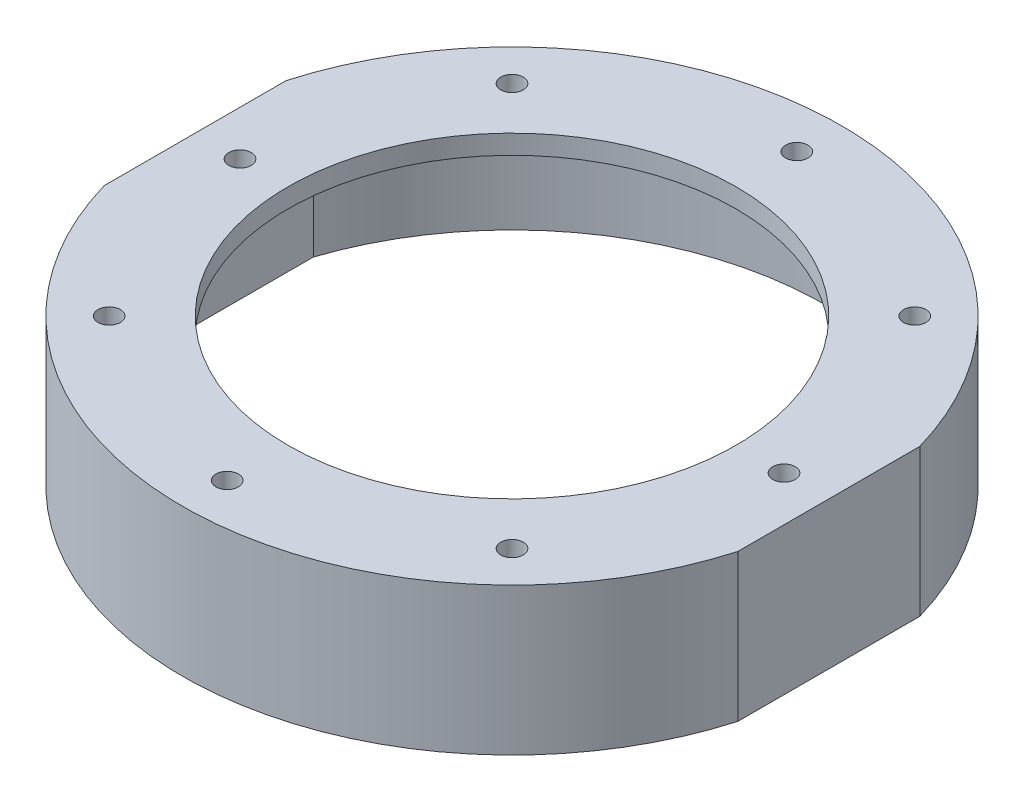
SolidWorks part; units mm, degrees
ref_plane "前视基准面" through (0, 0, 0) normal (0, 0, 1) x (1, 0, 0)
ref_plane "上视基准面" through (0, 0, 0) normal (0, 1, 0) x (1, 0, 0)
ref_plane "右视基准面" through (0, 0, 0) normal (1, 0, 0) x (0, 0, -1)
other "Configuration Table"
sketch "草图1" plane through (0, 0, 0) normal (0, 1, 0) x (1, 0, 0)
  line L1 (-46.5, -20.9132) -> (46.5, -20.9132)
  line L2 (-46.5, -20.9132) -> (-46.5, 20.9132)
  line L3 (-46.5, 20.9132) -> (46.5, 20.9132)
  line L4 (46.5, -20.9132) -> (46.5, 20.9132)
  line L5 (-46.5, -20.9132) -> (46.5, 20.9132) construction
  line L6 (-46.5, 20.9132) -> (46.5, -20.9132) construction
  circle A0 centre (0, 0) radius 49
  circle A1 centre (0, 0) radius 52
  dimension "D1" = 98
  dimension "D2" = 93
  dimension "D3" = 3
extrude "凸台-拉伸1" add sketch "草图1" along normal blind 20 contours A0 L2 L1 | A1 A0 L4 L1 L2 L3 | A0 L3 L2 | L2 A0 | L4 A0 | A0 L1 L4 | A0 L4 L3
sketch "草图2" plane through (0, 20, 0) normal (0, 1, 0) x (1, 0, 0)
  circle A0 centre (0, 0) radius 51.5
  circle A1 centre (0, 0) radius 52
  dimension "D1" = 103
extrude "切除-拉伸1" cut sketch "草图2" against normal blind 20
sketch "草图3" plane through (0, 20, 0) normal (0, 1, 0) x (1, 0, 0)
  circle A0 centre (0, 0) radius 51.5
  circle A1 centre (0, 0) radius 42.5
  circle A2 centre (0, 42.5) radius 1.75
  circle A3 centre (30.052, 30.052) radius 1.75
  circle A4 centre (42.5, 0) radius 1.75
  circle A5 centre (30.052, -30.052) radius 1.75
  circle A6 centre (0, -42.5) radius 1.75
  circle A7 centre (-30.052, -30.052) radius 1.75
  circle A8 centre (-42.5, 0) radius 1.75
  circle A9 centre (-30.052, 30.052) radius 1.75
  circle A10 centre (0, 0) radius 35
  point P22 (0, 0)
  arc M1 (-46.5, 15.4515) -> (46.5, 15.4515) centre (0, 0) cw
  line M2 (46.5, 15.4515) -> (46.5, -15.4515)
  arc M3 (46.5, -15.4515) -> (-46.5, -15.4515) centre (0, 0) cw
  line M4 (-46.5, -15.4515) -> (-46.5, 15.4515)
  circle M5 centre (0, 0) radius 51.5
  dimension "D1" = 85
  dimension "D2" = 3.5
  dimension "D4" = 70
  dimension "D3" = 8
extrude "凸台-拉伸2" add sketch "草图3" along normal blind 3 contours A9 A1 A8 A7 A6 A5 A4 A3 A2 A10 | A9 A1 A2 A3 A4 A5 A6 A7 A8 M1 M4 M3 M2 | M5 M4 M1 M2 M3
sketch "草图4" plane through (0, 0, 0) normal (0, -1, 0) x (1, 0, 0)
  line L8 (-49.5, 15.4515) -> (-49.5, -15.4515)
  line L9 (-49.5, 15.4515) -> (-49.5, -15.4515)
  line L11 (49.5, 15.4515) -> (49.5, -15.4515)
  line L12 (49.5, 15.4515) -> (49.5, -15.4515)
  line L13 (49.5, -15.4515) -> (60.5775, -15.4515)
  line L14 (49.5, -15.4515) -> (49.5, 15.4515)
  line L15 (49.5, 15.4515) -> (60.5775, 15.4515)
  line L16 (60.5775, -15.4515) -> (60.5775, 15.4515)
  line L17 (-49.5, -15.4515) -> (-56.1561, -15.4515)
  line L18 (-49.5, -15.4515) -> (-49.5, 15.4515)
  line L19 (-49.5, 15.4515) -> (-56.1561, 15.4515)
  line L20 (-56.1561, -15.4515) -> (-56.1561, 15.4515)
  circle M8 centre (0, 0) radius 51.5
  dimension "D2" = 3
  dimension "D1" = 3
extrude "切除-拉伸2" cut sketch "草图4" against normal through all contours L13 L16 L15 L12 M8 | L12 M8 | L9 M8
sketch "草图6" plane through (0, 23, 0) normal (0, 1, 0) x (1, 0, 0)
  circle A0 centre (-30.052, 30.052) radius 1.75
  circle A1 centre (0, 42.5) radius 1.75
  circle A2 centre (30.052, 30.052) radius 1.75
  circle A3 centre (30.052, -30.052) radius 1.891
  circle A4 centre (0, -42.5) radius 1.75
  circle A5 centre (-30.052, -30.052) radius 1.75
extrude "凸台-拉伸3" add sketch "草图6" against normal blind 3
sketch "草图7" plane through (0, 23, 0) normal (0, 1, 0) x (1, 0, 0)
  circle A1 centre (0, 44.5) radius 1.75
  circle A2 centre (31.4663, 31.4663) radius 1.75
  circle A4 centre (31.4663, -31.4663) radius 1.75
  circle A5 centre (0, -44.5) radius 1.75
  circle A6 centre (-31.4663, -31.4663) radius 1.75
  circle A8 centre (-31.4663, 31.4663) radius 1.75
  circle A9 centre (-44.5, 0) radius 1.75 [skipped]
  circle A10 centre (44.5, 0) radius 1.75 [skipped]
  point P22 (0, 0)
  dimension "D2" = 3.5
  dimension "D3" = 8
extrude "切除-拉伸3" cut sketch "草图7" against normal blind 3
